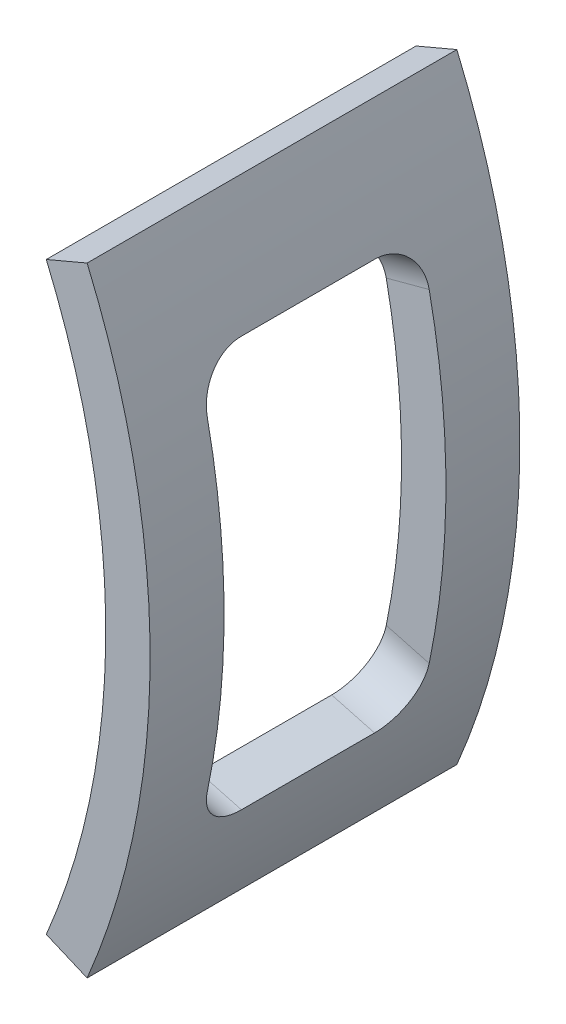
SolidWorks part; units mm, degrees
ref_plane "Front Plane" through (0, 0, 0) normal (0, 0, 1) x (1, 0, 0)
ref_plane "Top Plane" through (0, 0, 0) normal (0, 1, 0) x (1, 0, 0)
ref_plane "Right Plane" through (0, 0, 0) normal (1, 0, 0) x (0, 0, -1)
sketch "Sketch3" plane through (0, 0, 0) normal (0, 1, 0) x (1, 0, 0)
  line L0 (-55, 0) -> (55, 0) construction
  line L1 (107.15, -25) -> (101.15, -25)
  line L2 (107.15, -25) -> (107.15, 25)
  line L3 (107.15, 25) -> (101.15, 25)
  line L4 (101.15, -25) -> (101.15, 25)
  line L5 (107.15, -25) -> (101.15, 25) construction
  line L6 (107.15, 25) -> (101.15, -25) construction
  line L7 (0, -17.7188) -> (0, 12.8438) construction
  line L8 (0, -55) -> (0, 55) construction
  point P0 (104.15, 0)
  dimension "D1" = 6
  dimension "D2" = 50
  dimension "D3" = 25
  dimension "D4" = 202.3
revolve "Revolve1" add sketch "Sketch3" angle 23 about L7
sketch "Sketch4" plane through (0, 0, 0) normal (0, 1, 0) x (1, 0, 0)
  line L0 (-46.0535, 0) -> (46.0535, 0) construction
  line L1 (107.15, -15) -> (101.15, -15)
  line L2 (107.15, -15) -> (107.15, 15)
  line L3 (107.15, 15) -> (101.15, 15)
  line L4 (101.15, -15) -> (101.15, 15)
  line L5 (107.15, -15) -> (101.15, 15) construction
  line L6 (107.15, 15) -> (101.15, -15) construction
  line L7 (0, -27.5) -> (0, 27.5) construction
  line L8 (0, -15) -> (0, 15) construction
  point P0 (104.15, 0)
  dimension "D1" = 6
  dimension "D2" = 101.15
  dimension "D3" = 30
revolve "Cut-Revolve1" cut sketch "Sketch4" angle 15 about L8 other way angle 15
fillet "Fillet1" radius 6 4 edges at (100.6012, -26.956, -15) (100.6012, -26.956, 15) (100.6012, 26.956, -15) (100.6012, 26.956, 15)
